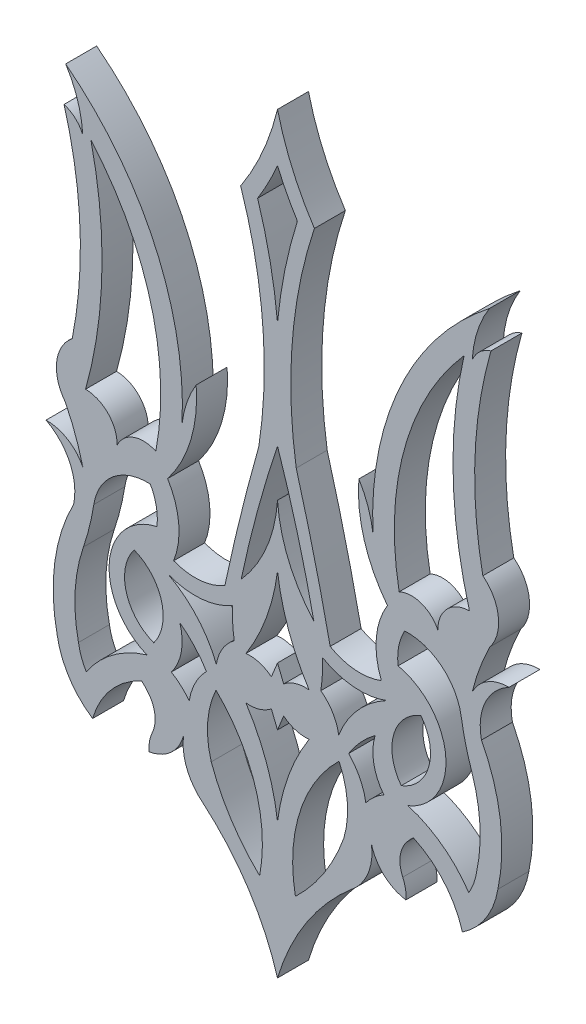
SolidWorks part; units mm, degrees
ref_plane "Спереди" through (0, 0, 0) normal (0, 0, 1) x (1, 0, 0)
ref_plane "Сверху" through (0, 0, 0) normal (0, 1, 0) x (1, 0, 0)
ref_plane "Справа" through (0, 0, 0) normal (1, 0, 0) x (0, 0, -1)
sketch "Эскиз3" plane through (0, 0, 0) normal (0, 0, 1) x (1, 0, 0)
  line L0 (87.6443, -0.7518) -> (87.6443, -30.7439) construction
  line L1 (75.7373, 214.8271) -> (99.5514, 214.8271) construction
  line L2 (87.6443, 214.8271) -> (87.6443, 245.1652) construction
  arc A0 (75.7373, 214.8271) -> (87.6443, 242.1865) centre (3.1746, 262.6778) ccw
  arc A2 (75.7373, 214.8271) -> (81.6055, 144.874) centre (-65.9765, 167.7164) cw
  arc A3 (81.6055, 144.874) -> (70.6377, 100.4834) centre (729.5469, -38.7656) ccw
  arc A4 (70.6377, 100.4834) -> (54.1195, 99.18) centre (61.0278, 116.9518) cw
  arc A5 (54.1195, 99.18) -> (52.147, 121.1645) centre (31.2493, 108.2088) ccw
  arc A6 (52.147, 121.1645) -> (61.3729, 151.9663) centre (17.0866, 148.4485) ccw
  arc A7 (61.3729, 151.9663) -> (56.8067, 138.8308) centre (89.4398, 134.8482) ccw
  arc A8 (56.8067, 138.8308) -> (19.2332, 220.6949) centre (-40.5564, 143.6983) ccw
  arc A9 (19.2332, 220.6949) -> (24.7593, 203.6092) centre (-10.9905, 201.483) cw
  arc A10 (24.7593, 203.6092) -> (18.7084, 209.1008) centre (15.8046, 199.8218) ccw
  arc A11 (18.7084, 209.1008) -> (21.3399, 144.8893) centre (-112.1058, 171.5801) cw
  arc A12 (21.3399, 144.8893) -> (19.102, 126.0824) centre (29.6244, 134.3669) ccw
  arc A13 (19.102, 126.0824) -> (24.7805, 110.6673) centre (-47.0296, 92.9675) cw
  arc A14 (24.7805, 110.6673) -> (12.8982, 117.9136) centre (13.0914, 104.8649) ccw
  arc A15 (12.8982, 117.9136) -> (21.781, 98.7337) centre (4.7748, 102.5045) cw
  arc A16 (21.781, 98.7337) -> (16.4854, 59.6475) centre (73.3534, 71.8446) ccw
  arc A17 (16.4854, 59.6475) -> (27.9301, 41.9549) centre (42.5937, 63.9882) ccw
  arc A18 (27.9301, 41.9549) -> (43.7562, 60.4021) centre (55.9548, 33.9245) cw
  arc A19 (43.7562, 60.4021) -> (46.0707, 57.9309) centre (32.5904, 47.6247) cw
  arc A20 (47.2033, 47.6608) -> (46.2055, 41.7904) centre (57.5332, 42.885) ccw
  arc A21 (46.2055, 41.7904) -> (57.3048, 51.8905) centre (44.028, 55.3321) ccw
  arc A22 (57.3048, 51.8905) -> (63.4952, 36.2204) centre (74.3192, 49.5541) ccw
  arc A23 (63.4952, 36.2204) -> (87.6443, -0.7518) centre (13.2717, -22.957) cw
  arc A24 (111.7935, 36.2204) -> (87.6443, -0.7518) centre (162.017, -22.957) ccw
  arc A25 (117.9838, 51.8905) -> (111.7935, 36.2204) centre (100.9695, 49.5541) cw
  arc A26 (129.0831, 41.7904) -> (117.9838, 51.8905) centre (131.2607, 55.3321) cw
  arc A27 (128.0854, 47.6608) -> (129.0831, 41.7904) centre (117.7555, 42.885) cw
  arc A28 (131.5325, 60.4021) -> (129.218, 57.9309) centre (142.6983, 47.6247) ccw
  arc A29 (147.3585, 41.9549) -> (131.5325, 60.4021) centre (119.3338, 33.9245) ccw
  arc A30 (158.8033, 59.6475) -> (147.3585, 41.9549) centre (132.695, 63.9882) cw
  arc A31 (153.5077, 98.7337) -> (158.8033, 59.6475) centre (101.9353, 71.8446) cw
  arc A32 (162.3905, 117.9136) -> (153.5077, 98.7337) centre (170.5139, 102.5045) ccw
  arc A33 (150.5081, 110.6673) -> (162.3905, 117.9136) centre (162.1973, 104.8649) cw
  arc A34 (156.1867, 126.0824) -> (150.5081, 110.6673) centre (222.3183, 92.9675) ccw
  arc A35 (153.9488, 144.8893) -> (156.1867, 126.0824) centre (145.6643, 134.3669) cw
  arc A36 (156.5803, 209.1008) -> (153.9488, 144.8893) centre (287.3945, 171.5801) ccw
  arc A37 (150.5293, 203.6092) -> (156.5803, 209.1008) centre (159.4841, 199.8218) cw
  arc A38 (156.0554, 220.6949) -> (150.5293, 203.6092) centre (186.2792, 201.483) ccw
  arc A39 (118.482, 138.8308) -> (156.0554, 220.6949) centre (215.8451, 143.6983) cw
  arc A40 (113.9158, 151.9663) -> (118.482, 138.8308) centre (85.8489, 134.8482) cw
  arc A41 (123.1417, 121.1645) -> (113.9158, 151.9663) centre (158.202, 148.4485) cw
  arc A42 (121.1692, 99.18) -> (123.1417, 121.1645) centre (144.0394, 108.2088) cw
  arc A43 (104.651, 100.4834) -> (121.1692, 99.18) centre (114.2609, 116.9518) ccw
  arc A44 (93.6832, 144.874) -> (104.651, 100.4834) centre (-554.2582, -38.7656) cw
  arc A45 (99.5514, 214.8271) -> (93.6832, 144.874) centre (241.2652, 167.7164) ccw
  arc A47 (99.5514, 214.8271) -> (87.6443, 242.1865) centre (172.1141, 262.6778) cw
  arc A48 (46.0707, 57.9309) -> (47.2033, 47.6608) centre (38.1265, 51.8573) cw
  arc A49 (129.218, 57.9309) -> (128.0854, 47.6608) centre (137.1622, 51.8573) ccw
  point P110 (49.2752, 50.7157)
  point P113 (126.0135, 50.7157)
  dimension "D1" = 10
  dimension "D2" = 10
extrude "Бобышка-Вытянуть1" add sketch "Эскиз3" along normal blind 10
sketch "Эскиз4" plane through (0, 0, 0) normal (0, 0, 1) x (1, 0, 0)
  line L0 (87.6443, -0.7518) -> (87.6443, -32.3218) construction
  line L1 (85.6546, 73.5186) -> (87.6443, 68.6318)
  line L2 (87.6443, 68.6318) -> (89.6341, 73.5186)
  line L3 (73.672, 78) -> (99.3785, 78) construction
  line L4 (87.6443, 87.3682) -> (89.6341, 82.4814)
  line L5 (85.6546, 82.4814) -> (87.6443, 87.3682)
  arc A0 (87.6443, 148.0034) -> (75.9102, 104.8888) centre (451.7712, 25.7481) ccw
  arc A1 (87.6443, 132.8603) -> (75.9102, 104.8888) centre (41.1732, 135.9081) cw
  arc A2 (67.7808, 69.8254) -> (81.8714, 24.9568) centre (33.1175, 34.2929) cw
  arc A3 (81.8714, 24.9568) -> (66.2431, 49.0031) centre (124.8767, 70.0089) cw
  arc A4 (66.2431, 49.0031) -> (67.7808, 69.8254) centre (94.1751, 57.4083) cw
  arc A5 (87.6443, 42.9742) -> (77.4425, 71.0893) centre (20.2867, 34.4413) ccw
  arc A7 (64.6822, 73.5186) -> (56.1084, 82.846) centre (35.8416, 55.6125) ccw
  arc A8 (64.6822, 73.5186) -> (59.1188, 62.4923) centre (79.1678, 59.2931) ccw
  arc A9 (53.3348, 67.6488) -> (56.1084, 82.846) centre (40.0944, 77.917) ccw
  arc A10 (59.1188, 62.4923) -> (53.3348, 67.6488) centre (43.2754, 50.5432) ccw
  arc A12 (67.908, 77.0685) -> (52.3079, 94.5198) centre (36.5563, 64.7406) ccw
  arc A13 (67.908, 77.0685) -> (73.672, 86.5781) centre (82.0844, 74.9775) cw
  arc A14 (73.672, 86.5781) -> (73.1577, 96.1649) centre (115.3568, 93.6216) cw
  arc A15 (41.3552, 95.8164) -> (47.6907, 73.0153) centre (35.854, 82.0071) cw
  arc A16 (41.3552, 95.8164) -> (47.6907, 73.0153) centre (52.9673, 86.7622) ccw
  arc A27 (133.9335, 95.8164) -> (127.598, 73.0153) centre (122.3214, 86.7622) cw
  arc A28 (133.9335, 95.8164) -> (127.598, 73.0153) centre (139.4347, 82.0071) ccw
  arc A29 (101.6166, 86.5781) -> (102.131, 96.1649) centre (59.9318, 93.6216) ccw
  arc A30 (107.3806, 77.0685) -> (101.6166, 86.5781) centre (93.2043, 74.9775) ccw
  arc A31 (107.3806, 77.0685) -> (122.9808, 94.5198) centre (138.7324, 64.7406) cw
  arc A33 (116.1699, 62.4923) -> (121.9539, 67.6488) centre (132.0132, 50.5432) cw
  arc A34 (121.9539, 67.6488) -> (119.1803, 82.846) centre (135.1943, 77.917) cw
  arc A35 (110.6065, 73.5186) -> (116.1699, 62.4923) centre (96.1209, 59.2931) cw
  arc A36 (110.6065, 73.5186) -> (119.1803, 82.846) centre (139.4471, 55.6125) cw
  arc A38 (87.6443, 42.9742) -> (97.8462, 71.0893) centre (155.002, 34.4413) cw
  arc A39 (109.0456, 49.0031) -> (107.5079, 69.8254) centre (81.1136, 57.4083) ccw
  arc A40 (93.4173, 24.9568) -> (109.0456, 49.0031) centre (50.412, 70.0089) ccw
  arc A41 (107.5079, 69.8254) -> (93.4173, 24.9568) centre (142.1712, 34.2929) ccw
  arc A42 (87.6443, 132.8603) -> (99.3785, 104.8888) centre (134.1154, 135.9081) ccw
  arc A43 (87.6443, 148.0034) -> (99.3785, 104.8888) centre (-276.4825, 25.7481) cw
  arc A44 (77.4425, 71.0893) -> (85.6546, 73.5186) centre (78.6188, 82.2081) ccw
  arc A45 (97.8462, 71.0893) -> (89.6341, 73.5186) centre (96.6699, 82.2081) cw
  arc A46 (46.5701, 116.8463) -> (28.3164, 101.9946) centre (45.7021, 99.2698) ccw
  arc A47 (24.9573, 88.4367) -> (28.3164, 101.9946) centre (-50.7188, 114.3815) ccw
  arc A49 (48.7004, 106.02) -> (45.4623, 68.5209) centre (52.9673, 86.7622) ccw
  arc A50 (37.4121, 98.8909) -> (45.899, 68.3473) centre (52.9673, 86.7622) ccw construction
  arc A51 (87.6443, 113.0258) -> (77.4425, 84.9107) centre (20.2867, 121.5587) cw
  arc A52 (151.923, 60.9491) -> (149.4021, 53.997) centre (132.695, 63.9882) cw
  arc A53 (47.6085, 101.7505) -> (46.1975, 117.4761) centre (31.2493, 108.2088) ccw
  arc A54 (48.7004, 106.02) -> (46.5701, 116.8463) centre (31.2493, 108.2088) ccw
  arc A55 (129.8264, 68.5209) -> (149.4021, 53.997) centre (119.3338, 33.9245) cw
  arc A56 (150.3314, 88.4367) -> (146.9723, 101.9946) centre (226.0075, 114.3815) cw
  arc A57 (150.3314, 88.4367) -> (151.923, 60.9491) centre (101.9353, 71.8446) cw
  arc A58 (126.5883, 106.02) -> (129.8264, 68.5209) centre (122.3214, 86.7622) cw
  arc A59 (128.7186, 116.8463) -> (146.9723, 101.9946) centre (129.5865, 99.2698) cw
  arc A60 (126.5883, 106.02) -> (128.7186, 116.8463) centre (144.0394, 108.2088) cw
  arc A61 (87.6443, 113.0258) -> (97.8462, 84.9107) centre (155.002, 121.5587) ccw
  arc A62 (97.8462, 84.9107) -> (89.6341, 82.4814) centre (96.6699, 73.7919) ccw
  arc A63 (77.4425, 84.9107) -> (85.6546, 82.4814) centre (78.6188, 73.7919) cw
  arc A75 (28.3709, 96.2178) -> (16.1626, 124.1058) centre (4.7748, 102.5045) ccw
  arc A76 (23.3657, 60.9491) -> (25.8866, 53.997) centre (42.5937, 63.9882) ccw
  arc A77 (28.3709, 96.2178) -> (23.3657, 60.9491) centre (73.3534, 71.8446) ccw
  arc A78 (40.8271, 66.7598) -> (25.8866, 53.997) centre (55.9548, 33.9245) ccw
  arc A80 (23.3657, 60.9491) -> (25.8866, 53.997) centre (42.5937, 63.9882) ccw
  arc A81 (24.9573, 88.4367) -> (23.3657, 60.9491) centre (73.3534, 71.8446) ccw
  arc A82 (45.4623, 68.5209) -> (25.8866, 53.997) centre (55.9548, 33.9245) ccw
  arc A266 (49.8154, 139.1803) -> (14.94, 215.166) centre (-40.5564, 143.6983) ccw
  arc A267 (48.3554, 126.9004) -> (27.3869, 203.4577) centre (-40.5564, 143.6983) ccw
  arc A268 (25.6623, 132.9232) -> (35.854, 122.3882) centre (25.4906, 122.5599) cw
  arc A269 (28.204, 143.5164) -> (25.4371, 211.0307) centre (-112.1058, 171.5801) ccw
  arc A270 (25.6623, 132.9232) -> (27.3869, 203.4577) centre (-112.1058, 171.5801) ccw
  arc A271 (35.854, 122.3882) -> (48.3554, 126.9004) centre (44.3608, 118.3936) cw
  arc A279 (139.4347, 122.3882) -> (126.9333, 126.9004) centre (130.9279, 118.3936) ccw
  arc A280 (149.6264, 132.9232) -> (139.4347, 122.3882) centre (149.798, 122.5599) ccw
  arc A281 (149.6264, 132.9232) -> (147.9018, 203.4577) centre (287.3945, 171.5801) cw
  arc A282 (126.9333, 126.9004) -> (147.9018, 203.4577) centre (215.8451, 143.6983) cw
  arc A322 (94.0669, 214.1199) -> (88.742, 144.1093) centre (241.2652, 167.7164) ccw
  arc A323 (82.7853, 241.0077) -> (94.0669, 214.1199) centre (172.1141, 262.6778) ccw
  arc A324 (94.0669, 214.1199) -> (87.6443, 182.5908) centre (241.2652, 167.7164) ccw
  arc A325 (87.6443, 226.4274) -> (94.0669, 214.1199) centre (172.1141, 262.6778) ccw
  arc A328 (122.9808, 94.5198) -> (102.131, 96.1649) centre (114.2609, 116.9518) cw
  arc A329 (86.5466, 144.1093) -> (81.2218, 214.1199) centre (-65.9765, 167.7164) ccw
  arc A330 (81.2218, 214.1199) -> (92.5034, 241.0077) centre (3.1746, 262.6778) ccw
  arc A331 (87.6443, 182.5908) -> (81.2218, 214.1199) centre (-65.9765, 167.7164) ccw
  arc A332 (81.2218, 214.1199) -> (87.6443, 226.4274) centre (3.1746, 262.6778) ccw
  arc A333 (52.3079, 94.5198) -> (73.1577, 96.1649) centre (61.0278, 116.9518) ccw
  arc A334 (52.3079, 94.5198) -> (73.1577, 96.1649) centre (61.0278, 116.9518) ccw
  point P134 (28.7997, 106.8883)
  point P153 (48.7731, 116.5977)
  dimension "D7" = 5
  dimension "D8" = 80
  dimension "D9" = 7
  dimension "D10" = 78
  dimension "D1" = 7
  dimension "D2" = 7
  dimension "D3" = 7
  dimension "D4" = 5
  dimension "D5" = 5
  dimension "D6" = 5
extrude "Вырез-Вытянуть4" cut sketch "Эскиз4" along normal blind 10
scale "Масштаб1" scale about centroid uniform scaling yes scale factor 0.25
